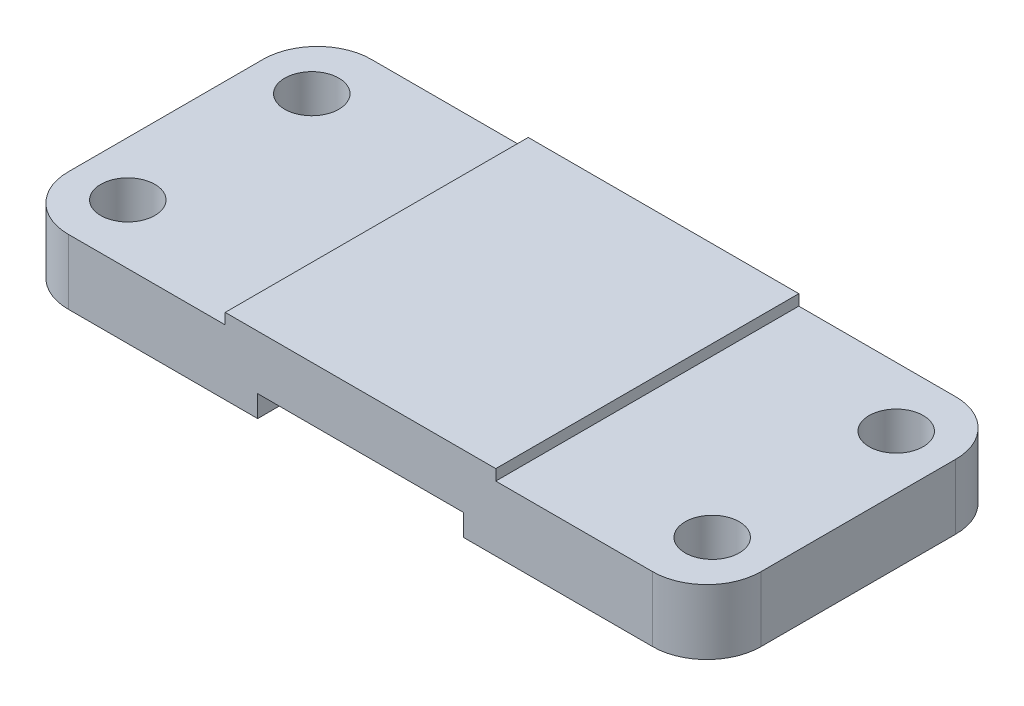
SolidWorks part; units mm, degrees
ref_plane "Ön Düzlem" through (0, 0, 0) normal (0, 0, 1) x (1, 0, 0)
ref_plane "Üst Düzlem" through (0, 0, 0) normal (0, 1, 0) x (1, 0, 0)
ref_plane "Sağ Düzlem" through (0, 0, 0) normal (1, 0, 0) x (0, 0, -1)
sketch "Çizim1" plane through (0, 0, 0) normal (0, 0, 1) x (1, 0, 0)
  line L0 (-33.4384, 12.2917) -> (11.5616, 12.2917)
  line L1 (-116.4384, 24.2917) -> (-77.4384, 24.2917)
  line L2 (-116.4384, 24.2917) -> (-116.4384, 12.2917)
  line L3 (-116.4384, 12.2917) -> (-71.4384, 12.2917)
  line L4 (11.5616, 24.2917) -> (11.5616, 12.2917)
  line L6 (-77.4384, 24.2917) -> (-77.4384, 26.2917)
  line L7 (-77.4384, 26.2917) -> (-27.4384, 26.2917)
  line L8 (-27.4384, 24.2917) -> (-27.4384, 26.2917)
  line L10 (-71.4384, 12.2917) -> (-71.4384, 16.2917)
  line L11 (-71.4384, 16.2917) -> (-33.4384, 16.2917)
  line L12 (-33.4384, 12.2917) -> (-33.4384, 16.2917)
  line L13 (-27.4384, 24.2917) -> (11.5616, 24.2917)
  dimension "D1" = 50
  dimension "D2" = 38
  dimension "D3" = 12
  dimension "D4" = 2
  dimension "D5" = 4
  dimension "D6" = 128
  dimension "D7" = 39
  dimension "D8" = 45
extrude "Yükseklik-Ekstrüzyon1" add sketch "Çizim1" along normal blind 56
fillet "Radyus1" radius 10 4 edges at (11.5616, 18.2917, 56) (11.5616, 18.2917, 0) (-116.4384, 18.2917, 0) (-116.4384, 18.2917, 56)
sketch "Çizim2" plane through (0, 24.2917, 0) normal (0, 1, 0) x (1, 0, 0)
  line L0 (1.5616, 0) -> (-27.4384, 0) construction
  line L1 (1.5616, -56) -> (-27.4384, -56) construction
  line L2 (-77.4384, 0) -> (-106.4384, 0) construction
  line L3 (-77.4384, -56) -> (-106.4384, -56) construction
  circle A0 centre (-106.4384, -11) radius 5
  circle A1 centre (-106.4384, -45) radius 5
  circle A2 centre (1.5616, -45) radius 5
  circle A3 centre (1.5616, -11) radius 5
  dimension "D1" = 10
  dimension "D2" = 10
  dimension "D3" = 10
  dimension "D4" = 10
  dimension "D6" = 11
  dimension "D5" = 56
  dimension "D7" = 11
  dimension "D8" = 34
  dimension "D9" = 11
  dimension "D10" = 11
  dimension "D11" = 34
  dimension "D12" = 108
extrude "Kes-Ekstrüzyon1" cut sketch "Çizim2" against normal through all
